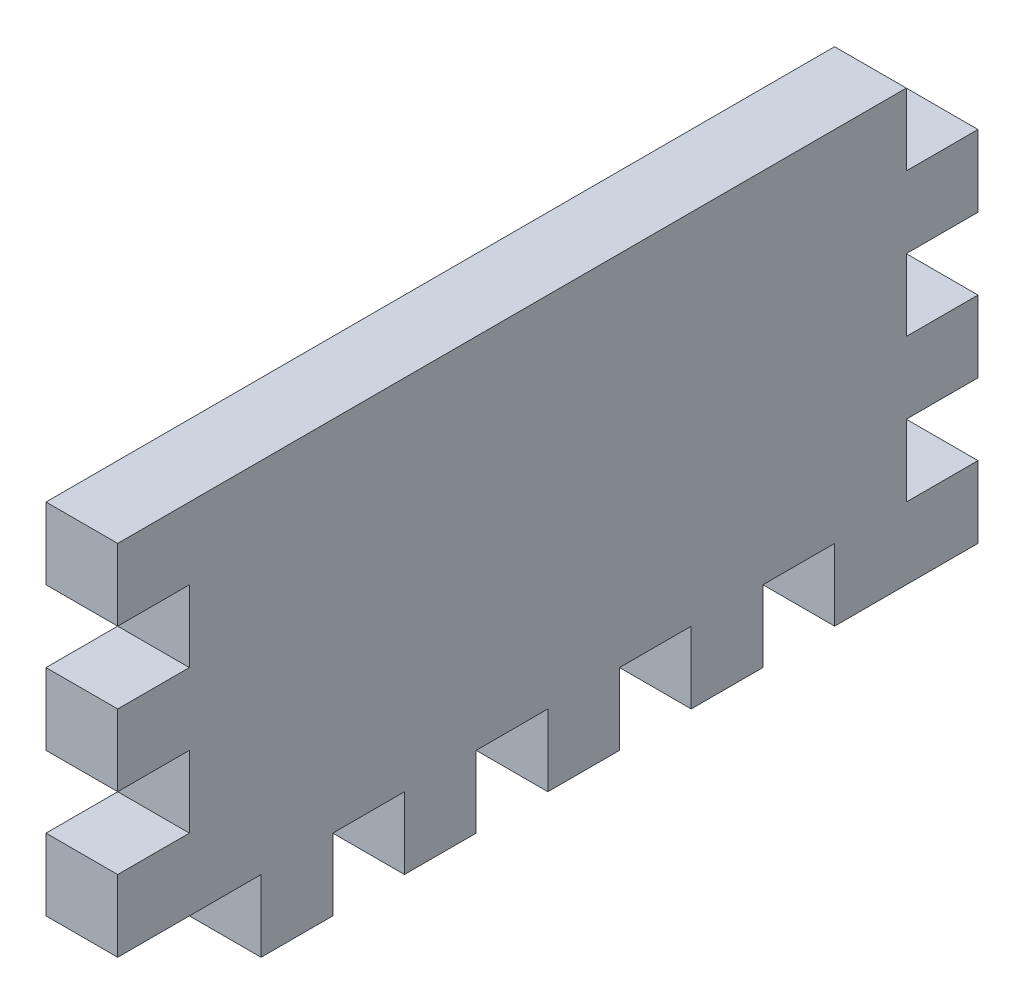
SolidWorks part; units mm, degrees
material "Mahogany"
ref_plane "Front Plane" through (0, 0, 0) normal (0, 0, 1) x (1, 0, 0)
ref_plane "Top Plane" through (0, 0, 0) normal (0, 1, 0) x (1, 0, 0)
ref_plane "Right Plane" through (0, 0, 0) normal (1, 0, 0) x (0, 0, -1)
sketch "Sketch1" plane through (0, 0, 0) normal (1, 0, 0) x (0, 0, -1)
  line L1 (-76.2, 38.1) -> (76.2, 38.1)
  line L2 (-76.2, 38.1) -> (-76.2, -38.1)
  line L3 (-76.2, -38.1) -> (76.2, -38.1)
  line L4 (76.2, 38.1) -> (76.2, -38.1)
  line L5 (-76.2, 38.1) -> (76.2, -38.1) construction
  line L6 (-76.2, -38.1) -> (76.2, 38.1) construction
  point P0 (0, 0)
  dimension "D1" = 152.4
  dimension "D2" = 76.2
extrude "Boss-Extrude1" add sketch "Sketch1" along normal blind 12.7
sketch "Sketch2" plane through (12.7, 0, 0) normal (1, 0, 0) x (0, 0, -1)
  line L0 (-76.2, 38.1) -> (-76.2, -38.1) construction
  line L1 (-76.2, 25.4) -> (-63.5, 25.4)
  line L2 (-76.2, 25.4) -> (-76.2, 12.7)
  line L3 (-76.2, 12.7) -> (-63.5, 12.7)
  line L4 (-63.5, 25.4) -> (-63.5, 12.7)
  line L5 (-76.2, 25.4) -> (-76.2, 38.1) construction
  line L6 (-76.2, 0) -> (-63.5, 0)
  line L7 (-76.2, 0) -> (-76.2, -12.7)
  line L8 (-76.2, -12.7) -> (-63.5, -12.7)
  line L9 (-63.5, 0) -> (-63.5, -12.7)
  line L10 (-76.2, -25.4) -> (-63.5, -25.4)
  line L11 (-76.2, -25.4) -> (-76.2, -38.1)
  line L12 (-76.2, -38.1) -> (-63.5, -38.1)
  line L13 (-63.5, -25.4) -> (-63.5, -38.1)
  line L14 (-76.2, 12.7) -> (-76.2, 0) construction
  line L15 (-76.2, -12.7) -> (-76.2, -25.4) construction
  line L16 (76.2, 38.1) -> (-76.2, 38.1) construction
  line L17 (76.2, -38.1) -> (76.2, 38.1) construction
  line L18 (76.2, 38.1) -> (63.5, 38.1)
  line L19 (76.2, 38.1) -> (76.2, 25.4)
  line L20 (76.2, 25.4) -> (63.5, 25.4)
  line L21 (63.5, 38.1) -> (63.5, 25.4)
  line L22 (76.2, 12.7) -> (63.5, 12.7)
  line L23 (76.2, 12.7) -> (76.2, 0)
  line L24 (76.2, 0) -> (63.5, 0)
  line L25 (63.5, 12.7) -> (63.5, 0)
  line L27 (76.2, -12.7) -> (63.5, -12.7)
  line L28 (76.2, -12.7) -> (76.2, -25.4)
  line L29 (76.2, -25.4) -> (63.5, -25.4)
  line L30 (63.5, -12.7) -> (63.5, -25.4)
  dimension "D1" = 12.7
  dimension "D2" = 12.7
  dimension "D3" = 12.7
extrude "Cut-Extrude1" cut sketch "Sketch2" against normal through all
extrude "Cut-Extrude2" cut sketch "Sketch3" against normal blind 12.7
sketch "Sketch3" plane through (90.4593, -38.1, 56.3344) normal (0, -1, 0) x (0, 0, 1)
  line L1 (-132.5344, 90.4593) -> (-119.8344, 90.4593)
  line L2 (-132.5344, 90.4593) -> (-132.5344, 103.1593)
  line L3 (-132.5344, 103.1593) -> (-119.8344, 103.1593)
  line L4 (-119.8344, 90.4593) -> (-119.8344, 103.1593)
  line L6 (-132.5344, 115.8593) -> (-119.8344, 115.8593)
  line L7 (-132.5344, 115.8593) -> (-132.5344, 128.5593)
  line L8 (-132.5344, 128.5593) -> (-119.8344, 128.5593)
  line L9 (-119.8344, 115.8593) -> (-119.8344, 128.5593)
  line L10 (-126.1844, 103.1593) -> (-126.1844, 115.8593) construction
  line L11 (-132.5344, 141.2593) -> (-119.8344, 141.2593)
  line L12 (-132.5344, 141.2593) -> (-132.5344, 153.9593)
  line L13 (-132.5344, 153.9593) -> (-119.8344, 153.9593)
  line L14 (-119.8344, 141.2593) -> (-119.8344, 153.9593)
  line L15 (-132.5344, 166.6593) -> (-119.8344, 166.6593)
  line L16 (-132.5344, 166.6593) -> (-132.5344, 179.3593)
  line L17 (-132.5344, 179.3593) -> (-119.8344, 179.3593)
  line L18 (-119.8344, 166.6593) -> (-119.8344, 179.3593)
  line L19 (-132.5344, 192.0593) -> (-119.8344, 192.0593)
  line L20 (-132.5344, 192.0593) -> (-132.5344, 204.7593)
  line L21 (-132.5344, 204.7593) -> (-119.8344, 204.7593)
  line L22 (-119.8344, 192.0593) -> (-119.8344, 204.7593)
  line L23 (-132.5344, 217.4593) -> (-119.8344, 217.4593)
  line L24 (-132.5344, 217.4593) -> (-132.5344, 230.1593)
  line L25 (-132.5344, 230.1593) -> (-119.8344, 230.1593)
  line L26 (-119.8344, 217.4593) -> (-119.8344, 230.1593)
  line L27 (-126.1844, 128.5593) -> (-126.1844, 141.2593) construction
  line L28 (-126.1844, 153.9593) -> (-126.1844, 166.6593) construction
  line L29 (-126.1844, 179.3593) -> (-126.1844, 192.0593) construction
  line L30 (-126.1844, 204.7593) -> (-126.1844, 217.4593) construction
  line L31 (-126.1844, 230.1593) -> (-126.1844, 242.8593) construction
  line L32 (-119.8344, 242.8593) -> (-132.5344, 242.8593)
  line L33 (-119.8344, 242.8593) -> (-119.8344, 255.5593)
  line L34 (-119.8344, 255.5593) -> (-132.5344, 255.5593)
  line L35 (-132.5344, 242.8593) -> (-132.5344, 255.5593)
  line L36 (-119.8344, 242.8593) -> (-132.5344, 242.8593)
  line L37 (-119.8344, 242.8593) -> (-119.8344, 255.5593)
  line L38 (-119.8344, 255.5593) -> (-132.5344, 255.5593)
  line L39 (-132.5344, 242.8593) -> (-132.5344, 255.5593)
  line L40 (-126.1844, 255.5593) -> (-126.1844, 242.8593) construction
  line L42 (-107.1344, 90.4593) -> (-94.4344, 90.4593)
  line L43 (-107.1344, 90.4593) -> (-107.1344, 77.7593)
  line L44 (-107.1344, 77.7593) -> (-94.4344, 77.7593)
  line L45 (-94.4344, 90.4593) -> (-94.4344, 77.7593)
  line L47 (-94.4344, 84.1093) -> (-81.7344, 84.1093) construction
  line L48 (-81.7344, 90.4593) -> (-69.0344, 90.4593)
  line L49 (-81.7344, 90.4593) -> (-81.7344, 77.7593)
  line L50 (-81.7344, 77.7593) -> (-69.0344, 77.7593)
  line L51 (-69.0344, 90.4593) -> (-69.0344, 77.7593)
  line L52 (-56.3344, 90.4593) -> (-43.6344, 90.4593)
  line L53 (-56.3344, 90.4593) -> (-56.3344, 77.7593)
  line L54 (-56.3344, 77.7593) -> (-43.6344, 77.7593)
  line L55 (-43.6344, 90.4593) -> (-43.6344, 77.7593)
  line L56 (-30.9344, 90.4593) -> (-18.2344, 90.4593)
  line L57 (-30.9344, 90.4593) -> (-30.9344, 77.7593)
  line L58 (-30.9344, 77.7593) -> (-18.2344, 77.7593)
  line L59 (-18.2344, 90.4593) -> (-18.2344, 77.7593)
  line L60 (-69.0344, 84.1093) -> (-56.3344, 84.1093) construction
  line L61 (-43.6344, 84.1093) -> (-30.9344, 84.1093) construction
  line L62 (-18.2344, 84.1093) -> (-5.5344, 84.1093) construction
  line L63 (-5.5344, 90.4593) -> (7.1656, 90.4593)
  line L64 (-5.5344, 90.4593) -> (-5.5344, 77.7593)
  line L65 (-5.5344, 77.7593) -> (7.1656, 77.7593)
  line L66 (7.1656, 90.4593) -> (7.1656, 77.7593)
